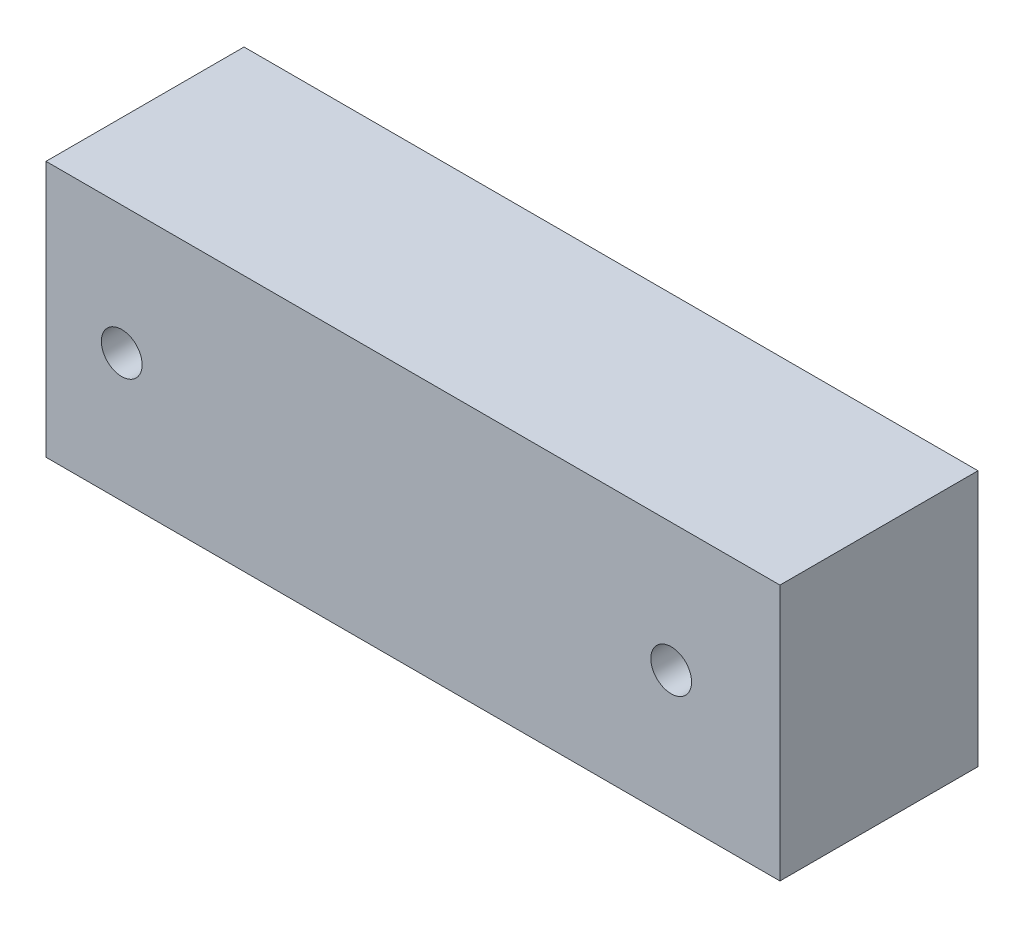
SolidWorks part; units mm, degrees
ref_plane "Front Plane" through (0, 0, 0) normal (0, 0, 1) x (1, 0, 0)
ref_plane "Top Plane" through (0, 0, 0) normal (0, 1, 0) x (1, 0, 0)
ref_plane "Right Plane" through (0, 0, 0) normal (1, 0, 0) x (0, 0, -1)
sketch "Sketch1" plane through (0, 0, 0) normal (0, 0, 1) x (1, 0, 0)
  line L1 (-31.5, 11) -> (31.5, 11)
  line L2 (-31.5, 11) -> (-31.5, -11)
  line L3 (-31.5, -11) -> (31.5, -11)
  line L4 (31.5, 11) -> (31.5, -11)
  line L5 (-31.5, 11) -> (31.5, -11) construction
  line L6 (-31.5, -11) -> (31.5, 11) construction
  point P0 (0, 0)
  dimension "D1" = 22
  dimension "D2" = 63
extrude "Boss-Extrude1" add sketch "Sketch1" along normal blind 17
sketch "Sketch2" plane through (0, 0, 17) normal (0, 0, 1) x (1, 0, 0)
  circle A0 centre (-25, 0) radius 1.75
  circle A1 centre (22.1656, 0) radius 1.75
  point P4 (0, 0)
  point P7 (-17.5477, -0.4002)
  dimension "D1" = 3.5
  dimension "D2" = 3.5
  dimension "D3" = 25
  dimension "25mm" = 22.1656
extrude "Cut-Extrude1" cut sketch "Sketch2" against normal through all
